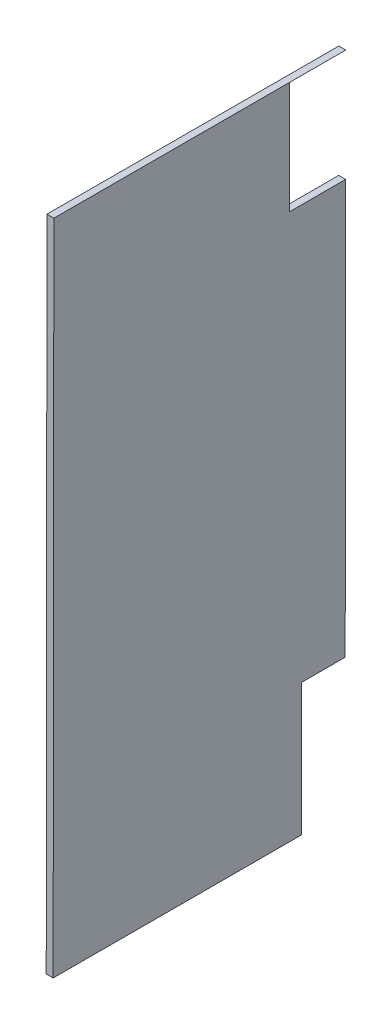
SolidWorks part; units mm, degrees
ref_plane "Front Plane" through (0, 0, 0) normal (0, 0, 1) x (1, 0, 0)
ref_plane "Top Plane" through (0, 0, 0) normal (0, 1, 0) x (1, 0, 0)
ref_plane "Right Plane" through (0, 0, 0) normal (1, 0, 0) x (0, 0, -1)
sketch "Sketch4" plane through (0, 0, 0) normal (1, 0, 0) x (0, 0, -1)
  line L4 (157.3416, 1482.6143) -> (157.2224, 1371.4894)
  line L5 (157.2224, 1371.4894) -> (188.1787, 1371.4562)
  line L6 (188.1787, 1371.4562) -> (188.2978, 1482.5811)
  line L7 (188.2978, 1482.5811) -> (157.3416, 1482.6143)
  line L8 (157.3416, 1482.6143) -> (157.2224, 1371.4894)
  line L9 (157.2224, 1371.4894) -> (188.1787, 1371.4562)
  line L10 (188.1787, 1371.4562) -> (188.2978, 1482.5811)
  line L11 (188.2978, 1482.5811) -> (157.3416, 1482.6143)
  line L12 (15.4227, 1243.2574) -> (15.2726, 1103.2575)
  line L13 (75.4227, 1243.1931) -> (15.4227, 1243.2574)
  line L14 (75.2725, 1103.1932) -> (75.4227, 1243.1931)
  line L15 (15.2726, 1103.2575) -> (75.2725, 1103.1932)
  line L16 (15.4227, 1243.2574) -> (15.2726, 1103.2575)
  line L17 (75.4227, 1243.1931) -> (15.4227, 1243.2574)
  line L18 (75.2725, 1103.1932) -> (75.4227, 1243.1931)
  line L19 (15.2726, 1103.2575) -> (75.2725, 1103.1932)
  line L20 (93.0445, 1185.1049) -> (92.9559, 1102.5549)
  line L21 (166.7044, 1185.0259) -> (93.0445, 1185.1049)
  line L22 (166.6159, 1102.4759) -> (166.7044, 1185.0259)
  line L23 (92.9559, 1102.5549) -> (166.6159, 1102.4759)
  line L24 (93.0445, 1185.1049) -> (92.9559, 1102.5549)
  line L25 (166.7044, 1185.0259) -> (93.0445, 1185.1049)
  line L26 (166.6159, 1102.4759) -> (166.7044, 1185.0259)
  line L27 (92.9559, 1102.5549) -> (166.6159, 1102.4759)
  line L28 (-1.3732, 1364.349) -> (-1.2477, 1481.3489)
  line L29 (-1.2477, 1481.3489) -> (-108.2477, 1481.4637)
  line L30 (-108.2477, 1481.4637) -> (-108.3731, 1364.4638)
  line L31 (-108.3731, 1364.4638) -> (-1.3732, 1364.349)
  line L32 (-1.3732, 1364.349) -> (-1.2477, 1481.3489)
  line L33 (-1.2477, 1481.3489) -> (-108.2477, 1481.4637)
  line L34 (-108.2477, 1481.4637) -> (-108.3731, 1364.4638)
  line L35 (-108.3731, 1364.4638) -> (-1.3732, 1364.349)
  line L36 (212.5445, 1095.146) -> (213.062, 1577.7457)
  line L37 (213.062, 1577.7457) -> (-1.1441, 1577.9754)
  line L38 (-1.1441, 1577.9754) -> (-1.6617, 1095.3757)
  line L39 (-1.6617, 1095.3757) -> (212.5445, 1095.146)
  line L40 (212.5445, 1095.146) -> (213.062, 1577.7457)
  line L41 (213.062, 1577.7457) -> (-1.1441, 1577.9754)
  line L42 (-1.1441, 1577.9754) -> (-1.6617, 1095.3757)
  line L43 (-1.6617, 1095.3757) -> (212.5445, 1095.146)
  line L44 (132.1558, 1496.8861) -> (132.2102, 1547.686)
  line L45 (22.1738, 1497.004) -> (132.1558, 1496.8861)
  line L46 (22.2283, 1547.804) -> (22.1738, 1497.004)
  line L47 (132.2102, 1547.686) -> (22.2283, 1547.804)
  line L48 (132.1558, 1496.8861) -> (132.2102, 1547.686)
  line L49 (22.1738, 1497.004) -> (132.1558, 1496.8861)
  line L50 (22.2283, 1547.804) -> (22.1738, 1497.004)
  line L51 (132.2102, 1547.686) -> (22.2283, 1547.804)
  circle A1 centre (119.3281, 1423.6745) radius 29.083
  circle A2 centre (119.3281, 1423.6745) radius 29.083
  circle A3 centre (200.4469, 1536.4842) radius 9.525
  circle A4 centre (200.4469, 1536.4842) radius 9.525
  circle A5 centre (200.0179, 1136.4344) radius 9.525
  circle A6 centre (200.0179, 1136.4344) radius 9.525
  circle A7 centre (50.6667, 1428.0165) radius 29.083
  circle A8 centre (50.6667, 1428.0165) radius 29.083
  dimension "D1" = 0
  dimension "D2" = 0
  dimension "D3" = 0
  dimension "D4" = 0
  dimension "D5" = 0
  dimension "D6" = 0
  dimension "D7" = 0
  dimension "D8" = 0
  dimension "D9" = 0
  dimension "D10" = 0
sketch "Sketch5" plane through (0, 0, 0) normal (1, 0, 0) x (0, 0, -1)
  line L1 (-1.6617, 1095.3757) -> (212.5445, 1095.146)
  line L2 (-1.6617, 1095.3757) -> (-1.1441, 1577.9754)
  line L3 (-1.1441, 1577.9754) -> (213.062, 1577.7457)
  line L4 (212.5445, 1095.146) -> (213.062, 1577.7457)
  line L5 (-1.6617, 1095.3757) -> (213.062, 1577.7457) construction
  line L6 (-1.1441, 1577.9754) -> (212.5445, 1095.146) construction
  line L8 (212.5445, 1095.146) -> (213.062, 1577.7457) construction
  line L9 (-1.3732, 1364.349) -> (-1.2477, 1481.3489) construction
  line L10 (213.062, 1577.7457) -> (-1.1441, 1577.9754) construction
  line L11 (-1.6617, 1095.3757) -> (212.5445, 1095.146) construction
  point P0 (105.7002, 1336.5607)
extrude "Boss-Extrude1" add sketch "Sketch5" along normal blind 5.08
sketch "Sketch6" plane through (5.08, 0, 0) normal (1, 0, 0) x (0, 0, -1)
  line L1 (22.2283, 1547.804) -> (132.1558, 1547.804)
  line L2 (22.2283, 1547.804) -> (22.2283, 1496.8861)
  line L3 (22.2283, 1496.8861) -> (132.1558, 1496.8861)
  line L4 (132.1558, 1547.804) -> (132.1558, 1496.8861)
  line L5 (157.3416, 1482.6143) -> (188.1787, 1482.6143)
  line L6 (157.3416, 1482.6143) -> (157.3416, 1371.4562)
  line L7 (157.3416, 1371.4562) -> (188.1787, 1371.4562)
  line L8 (188.1787, 1482.6143) -> (188.1787, 1371.4562)
  line L9 (75.4227, 1243.1931) -> (15.2726, 1243.1931)
  line L10 (75.4227, 1243.1931) -> (75.4227, 1103.2575)
  line L11 (75.4227, 1103.2575) -> (15.2726, 1103.2575)
  line L12 (15.2726, 1243.1931) -> (15.2726, 1103.2575)
  line L13 (93.0445, 1185.1049) -> (166.6159, 1185.1049)
  line L14 (93.0445, 1185.1049) -> (93.0445, 1102.4759)
  line L15 (93.0445, 1102.4759) -> (166.6159, 1102.4759)
  line L16 (166.6159, 1185.1049) -> (166.6159, 1102.4759)
  circle A0 centre (50.6667, 1428.0165) radius 29.083
  circle A1 centre (119.3281, 1423.6745) radius 29.083
sketch "Sketch7" plane through (5.08, 0, 0) normal (1, 0, 0) x (0, 0, -1)
  line L1 (-108.2477, 1481.4637) -> (-1.3732, 1481.4637)
  line L2 (-108.2477, 1481.4637) -> (-108.2477, 1364.349)
  line L3 (-108.2477, 1364.349) -> (-1.3732, 1364.349)
  line L4 (-1.3732, 1481.4637) -> (-1.3732, 1364.349)
  circle A0 centre (200.4469, 1536.4842) radius 9.525
  circle A1 centre (200.0179, 1136.4344) radius 9.525
sketch "Sketch11" plane through (5.08, 0, 0) normal (1, 0, 0) x (0, 0, -1)
  line L1 (213.062, 1577.7457) -> (171.741, 1577.7457)
  line L2 (213.062, 1577.7457) -> (213.062, 1495.5746)
  line L3 (213.062, 1495.5746) -> (171.741, 1495.5746)
  line L4 (171.741, 1577.7457) -> (171.741, 1495.5746)
  line L9 (180.4087, 1192.0781) -> (245.2674, 1192.0781)
  line L10 (180.4087, 1192.0781) -> (180.4087, 1060.8011)
  line L11 (180.4087, 1060.8011) -> (245.2674, 1060.8011)
  line L12 (245.2674, 1192.0781) -> (245.2674, 1060.8011)
extrude "Cut-Extrude1" cut sketch "Sketch11" against normal through all
